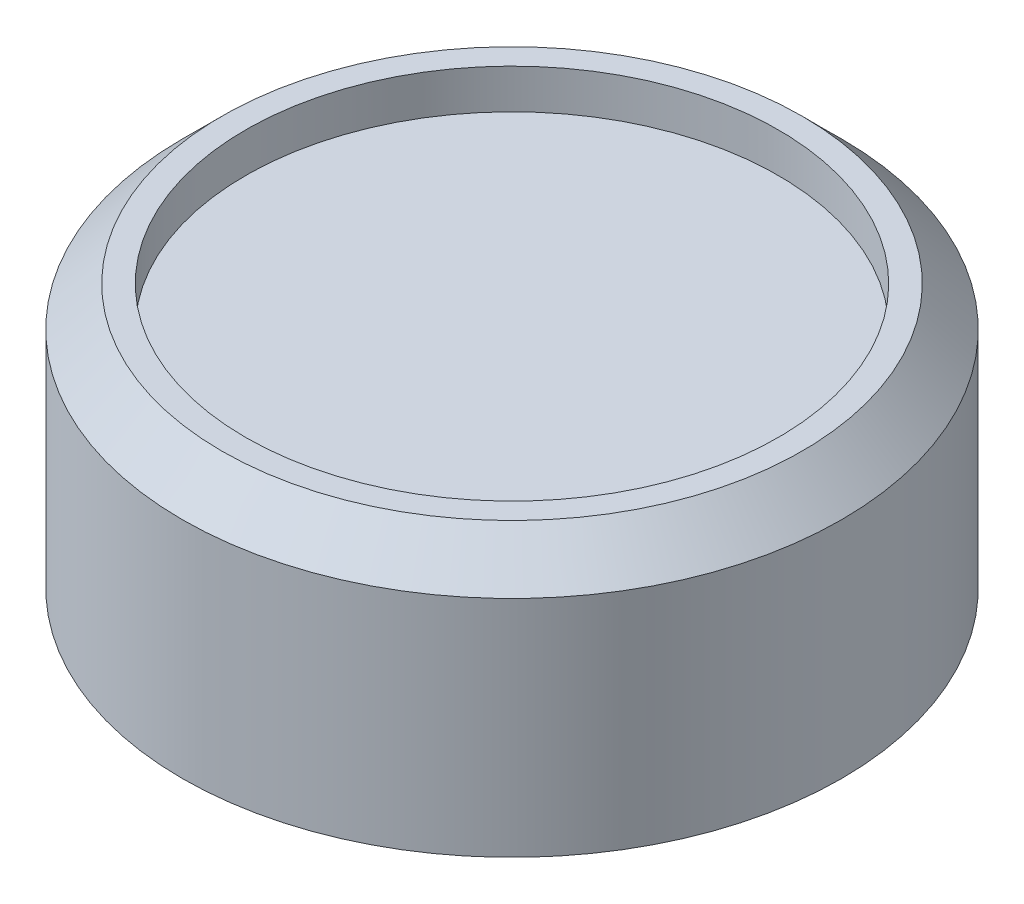
SolidWorks part; units mm, degrees
ref_plane "Front Plane" through (0, 0, 0) normal (0, 0, 1) x (1, 0, 0)
ref_plane "Top Plane" through (0, 0, 0) normal (0, 1, 0) x (1, 0, 0)
ref_plane "Right Plane" through (0, 0, 0) normal (1, 0, 0) x (0, 0, -1)
sketch "Sketch1" plane through (0, 0, 0) normal (0, 1, 0) x (1, 0, 0)
  circle A0 centre (0, 0) radius 12.5
  dimension "D1" = 25
extrude "Boss-Extrude1" add sketch "Sketch1" along normal blind 10
sketch "Sketch2" plane through (0, 0, 0) normal (0, -1, 0) x (1, 0, 0)
  line L1 (7.7365, 0) -> (3.8682, 6.7)
  line L2 (3.8682, 6.7) -> (-3.8682, 6.7)
  line L3 (-3.8682, 6.7) -> (-7.7365, 0)
  line L4 (-7.7365, 0) -> (-3.8682, -6.7)
  line L5 (-3.8682, -6.7) -> (3.8682, -6.7)
  line L6 (3.8682, -6.7) -> (7.7365, 0)
  circle A0 centre (0, 0) radius 6.7 construction
  dimension "D1" = 13.4
extrude "Cut-Extrude1" cut sketch "Sketch2" against normal blind 8
chamfer "Chamfer1" distance 1.5 angle 45 1 edges at (0, 10, 12.5)
ref_plane "Plane1" through (0, 2.3, 0) normal (0, -1, 0) x (-1, 0, 0)
sketch "Sketch5" plane through (0, 2.3, 0) normal (0, -1, 0) x (-1, 0, 0)
  circle A0 centre (0, 0) radius 10
  dimension "D1" = 20
extrude "Cut-Extrude2" cut sketch "Sketch5" along normal blind 6
sketch "Sketch6" plane through (0, 10, 0) normal (0, 1, 0) x (1, 0, 0)
  circle A0 centre (0, 0) radius 10.1
  dimension "D1" = 20.2
extrude "Cut-Extrude3" cut sketch "Sketch6" against normal blind 1.5
